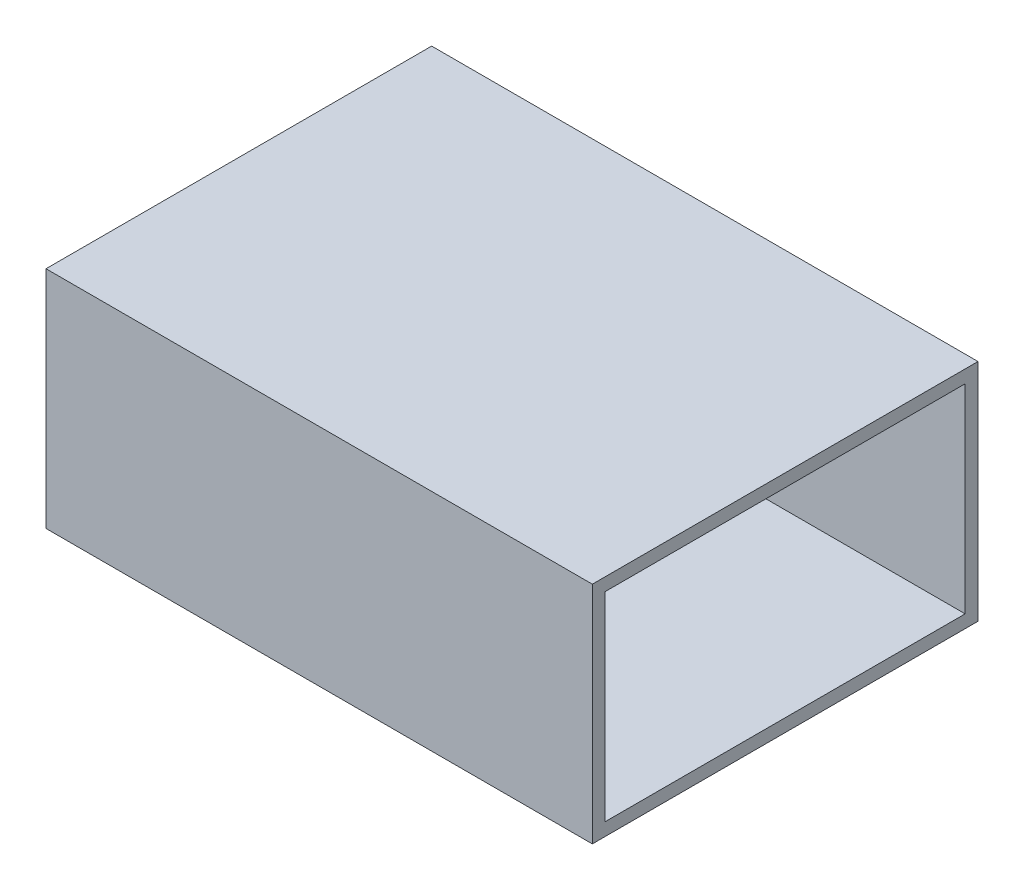
SolidWorks part; units mm, degrees
ref_plane "Front Plane" through (0, 0, 0) normal (0, 0, 1) x (1, 0, 0)
ref_plane "Top Plane" through (0, 0, 0) normal (0, 1, 0) x (1, 0, 0)
ref_plane "Right Plane" through (0, 0, 0) normal (1, 0, 0) x (0, 0, -1)
sketch "Sketch1" plane through (0, 0, 0) normal (0, 1, 0) x (1, 0, 0)
  line L1 (-42.5, -30) -> (42.5, -30)
  line L2 (-42.5, -30) -> (-42.5, 30)
  line L3 (-42.5, 30) -> (42.5, 30)
  line L4 (42.5, -30) -> (42.5, 30)
  line L5 (-42.5, -30) -> (42.5, 30) construction
  line L6 (-42.5, 30) -> (42.5, -30) construction
  point P0 (0, 0)
  dimension "D1" = 60
  dimension "D2" = 85
extrude "Boss-Extrude1" add sketch "Sketch1" along normal blind 35
sketch "Sketch2" plane through (42.5, 0, 0) normal (1, 0, 0) x (0, 0, -1)
  line L0 (30, 35) -> (30, 0) construction
  line L1 (-28, 2) -> (28, 2)
  line L2 (-28, 2) -> (-28, 33)
  line L3 (-28, 33) -> (28, 33)
  line L4 (28, 2) -> (28, 33)
  line L5 (-30, 35) -> (30, 35) construction
  line L6 (-30, 35) -> (-30, 0) construction
  line L7 (-30, 0) -> (30, 0) construction
  dimension "D1" = 2
  dimension "D2" = 2
  dimension "D3" = 2
  dimension "D4" = 2
extrude "Cut-Extrude1" cut sketch "Sketch2" against normal blind 80
